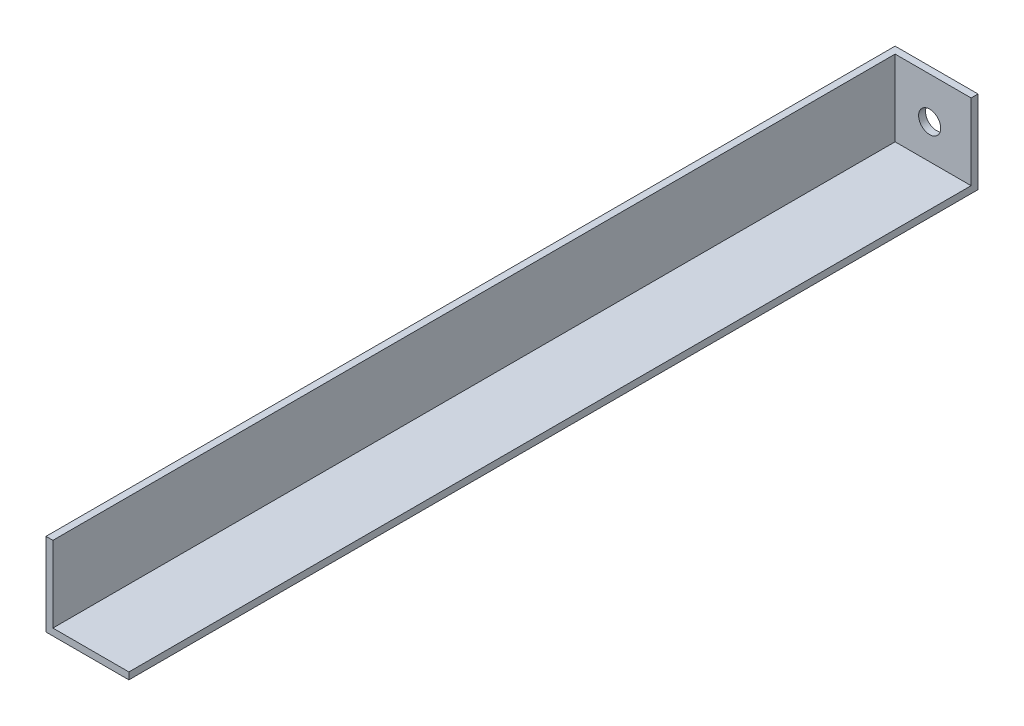
SolidWorks part; units mm, degrees
ref_plane "Front Plane" through (0, 0, 0) normal (0, 0, 1) x (1, 0, 0)
ref_plane "Top Plane" through (0, 0, 0) normal (0, 1, 0) x (1, 0, 0)
ref_plane "Right Plane" through (0, 0, 0) normal (1, 0, 0) x (0, 0, -1)
sketch "Sketch1" plane through (0, 0, 0) normal (0, 0, 1) x (1, 0, 0)
  line L0 (0, 0) -> (0, 30)
  line L1 (0, 30) -> (2.5, 30)
  line L2 (2.5, 30) -> (2.5, 2.5)
  line L3 (2.5, 2.5) -> (30, 2.5)
  line L4 (30, 2.5) -> (30, 0)
  line L5 (30, 0) -> (0, 0)
  dimension "D1" = 2.5
  dimension "D2" = 2.5
  dimension "D3" = 30
  dimension "D4" = 30
extrude "Boss-Extrude1" add sketch "Sketch1" along normal blind 304.8
sketch "Sketch2" plane through (0, 0, 0) normal (0, 0, -1) x (-1, 0, 0)
  line L1 (0, 0) -> (-30, 0)
  line L2 (0, 0) -> (0, 30)
  line L3 (0, 30) -> (-30, 30)
  line L4 (-30, 0) -> (-30, 30)
  dimension "D1" = 30
  dimension "D2" = 30
extrude "Boss-Extrude2" add sketch "Sketch2" along normal blind 2.5
sketch "Sketch3" plane through (0, 0, -2.5) normal (0, 0, -1) x (-1, 0, 0)
  line L0 (-30, 0) -> (0, 0) construction
  line L1 (0, 0) -> (0, 30) construction
  circle A0 centre (-15, 15) radius 4
  dimension "D1" = 8
  dimension "D2" = 15
  dimension "D3" = 15
extrude "Cut-Extrude1" cut sketch "Sketch3" against normal through all
